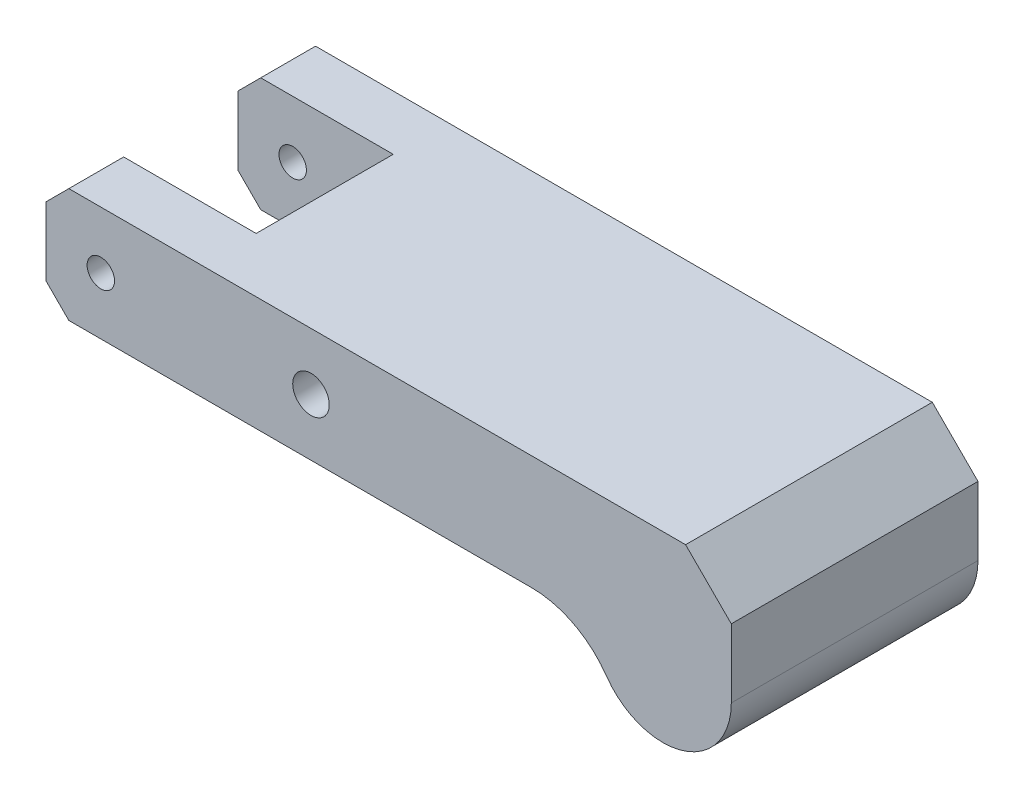
SolidWorks part; units mm, degrees
ref_plane "Piano frontale" through (0, 0, 0) normal (0, 0, 1) x (1, 0, 0)
ref_plane "Piano superiore" through (0, 0, 0) normal (0, 1, 0) x (1, 0, 0)
ref_plane "Piano destro" through (0, 0, 0) normal (1, 0, 0) x (0, 0, -1)
sketch "Schizzo1" plane through (0, 0, 0) normal (0, 0, 1) x (1, 0, 0)
  line L1 (75, -12.5) -> (-75, -12.5)
  line L2 (75, -12.5) -> (75, 12.5)
  line L3 (75, 12.5) -> (-75, 12.5)
  line L4 (-75, -12.5) -> (-75, 12.5)
  line L5 (75, -12.5) -> (-75, 12.5) construction
  line L6 (75, 12.5) -> (-75, -12.5) construction
  point P0 (0, 0)
  dimension "D1" = 150
  dimension "D2" = 25
extrude "Estrusione-Estrusione1" add sketch "Schizzo1" along normal blind 54
sketch "Schizzo2" plane through (0, 0, 0) normal (0, 0, -1) x (-1, 0, 0)
  line L0 (75, -12.5) -> (-75, -12.5) construction
  line L1 (-75, -12.5) -> (-75, 12.5) construction
  line L2 (-75, -12.5) -> (-31.2772, -12.5)
  arc A0 (-75, -12.5) -> (-47.6902, -21.0714) centre (-60, -12.5) ccw
  arc A1 (-31.2772, -12.5) -> (-47.6902, -21.0714) centre (-31.2772, -32.5) ccw
  dimension "D1" = 15
  dimension "D2" = 20
extrude "Estrusione-Estrusione2" add sketch "Schizzo2" against normal blind 54
sketch "Schizzo3" plane through (0, 12.5, 0) normal (0, 1, 0) x (1, 0, 0)
  line L0 (-75, -54) -> (-75, 0) construction
  line L1 (-75, -42) -> (-41, -42)
  line L2 (-75, -42) -> (-75, -12)
  line L3 (-75, -12) -> (-41, -12)
  line L4 (-41, -42) -> (-41, -12)
  line L5 (75, -54) -> (-75, -54) construction
  dimension "D1" = 30
  dimension "D2" = 34
  dimension "D3" = 12
extrude "Taglio-Estrusione1" cut sketch "Schizzo3" against normal blind 25
sketch "Schizzo4" plane through (0, 0, 0) normal (0, 0, -1) x (-1, 0, 0)
  line L0 (0, 0) -> (75, 0) construction
  line L1 (75, 12.5) -> (75, -12.5) construction
  circle A0 centre (17, 0) radius 4
  circle A1 centre (63, 0) radius 3
  dimension "D1" = 8
  dimension "D2" = 6
  dimension "D3" = 58
  dimension "D4" = 12
extrude "Taglio-Estrusione2" cut sketch "Schizzo4" against normal blind 54
chamfer "Smusso1" distance 5 angle 45 4 edges at (-75, 12.5, 6) (-75, 12.5, 48) (-75, -12.5, 48) (-75, -12.5, 6)
chamfer "Smusso2" distance 10 angle 45 1 edges at (75, 12.5, 27)
